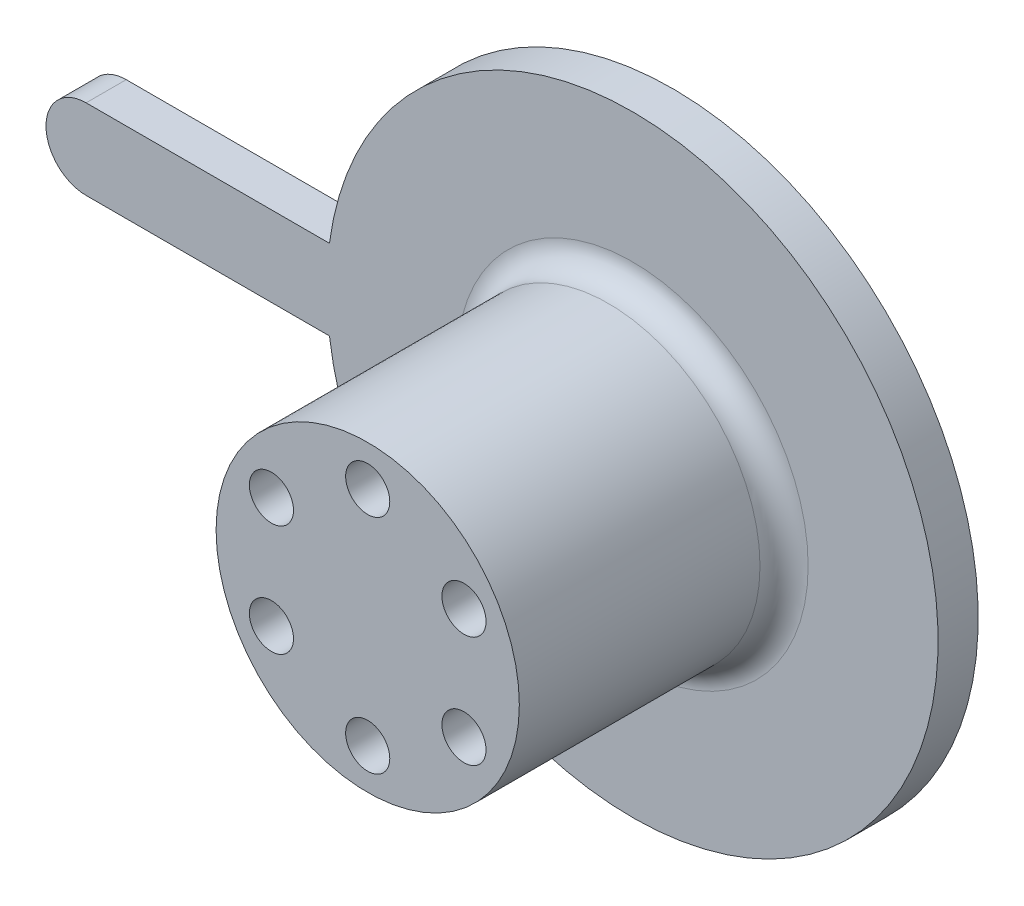
SolidWorks part; units mm, degrees
ref_plane "Front Plane" through (0, 0, 0) normal (0, 0, 1) x (1, 0, 0)
ref_plane "Top Plane" through (0, 0, 0) normal (0, 1, 0) x (1, 0, 0)
ref_plane "Right Plane" through (0, 0, 0) normal (1, 0, 0) x (0, 0, -1)
sketch "Sketch4" plane through (0, 0, 0) normal (0, 0, 1) x (1, 0, 0)
  line L0 (-38.1, 0) -> (-68.1, 0)
  line L1 (-68.1, 0) -> (-68.1, 5)
  line L2 (-68.1, 0) -> (-68.1, -5)
  line L3 (-68.1, 5) -> (-37.7705, 5)
  line L4 (-68.1, -5) -> (-37.7705, -5)
  circle A0 centre (0, 0) radius 38.1
  arc A1 (-68.1, 5) -> (-68.1, -5) centre (-68.1, 0) ccw
  dimension "D1" = 30
  dimension "D2" = 76.2
extrude "Boss-Extrude3" add sketch "Sketch4" along normal blind 5 contours A0 | A0 L3 L1 L0 | A0 L0 L2 L4 | L1 A1 L2
sketch "Sketch5" plane through (0, 0, 5) normal (0, 0, 1) x (1, 0, 0)
  circle A0 centre (0, 0) radius 18.9
extrude "Boss-Extrude4" add sketch "Sketch5" along normal blind 33
fillet "Fillet4" radius 3 1 edges at (18.9, 0, 5)
sketch "Sketch6" plane through (0, 0, 38) normal (0, 0, 1) x (1, 0, 0)
  line L1 (0, 13.8564) -> (-12, 6.9282)
  line L2 (-12, 6.9282) -> (-12, -6.9282)
  line L3 (-12, -6.9282) -> (0, -13.8564)
  line L4 (0, -13.8564) -> (12, -6.9282)
  line L5 (12, -6.9282) -> (12, 6.9282)
  line L6 (12, 6.9282) -> (0, 13.8564)
  circle A0 centre (0, 0) radius 12 construction
  circle A1 centre (0, 13.8564) radius 2.75
  circle A2 centre (12, 6.9282) radius 2.75
  circle A3 centre (12, -6.9282) radius 2.75
  circle A4 centre (0, -13.8564) radius 2.75
  circle A5 centre (-12, -6.9282) radius 2.75
  circle A6 centre (-12, 6.9282) radius 2.75
extrude "Cut-Extrude4" cut sketch "Sketch6" against normal blind 39.48 contours L6 A1 L1 | L1 A1 L6 | L5 A2 L6 | L6 A2 L5 | L4 A3 L5 | L5 A3 L4 | L1 A6 L2 | L2 A6 L1 | L3 A5 L2 | L2 A5 L3 | L3 A4 L4 | L4 A4 L3
